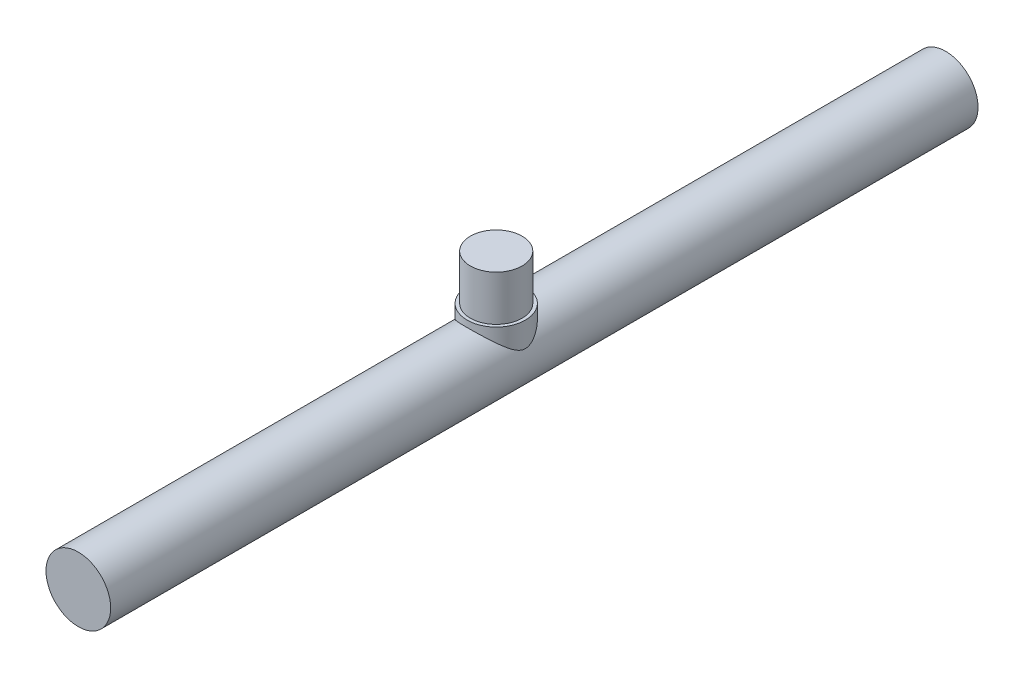
SolidWorks part; units mm, degrees
ref_plane "Front Plane" through (0, 0, 0) normal (0, 0, 1) x (1, 0, 0)
ref_plane "Top Plane" through (0, 0, 0) normal (0, 1, 0) x (1, 0, 0)
ref_plane "Right Plane" through (0, 0, 0) normal (1, 0, 0) x (0, 0, -1)
sketch "Sketch1" plane through (0, 0, 0) normal (0, 0, 1) x (1, 0, 0)
  circle A0 centre (0, 0) radius 5
  dimension "D1" = 10
extrude "Boss-Extrude1" add sketch "Sketch1" along normal blind 70
sketch "Sketch2" plane through (0, 0, 0) normal (0, 1, 0) x (1, 0, 0)
  circle A0 centre (0, -5.3867) radius 4.5
  dimension "D1" = 9
extrude "Boss-Extrude2" add sketch "Sketch2" along normal blind 6
sketch "Sketch3" plane through (0, 0, 0) normal (0, 0, -1) x (-1, 0, 0)
  circle A0 centre (0, 0) radius 5
extrude "Cut-Extrude2" cut sketch "Sketch3" against normal blind 0.8867
sketch "Sketch4" plane through (0, 6, 0) normal (0, 1, 0) x (1, 0, 0)
  circle A0 centre (0, -5.3867) radius 4
  dimension "D1" = 8
extrude "Boss-Extrude3" add sketch "Sketch4" along normal blind 7
sketch "Sketch5" plane through (0, 0, 0.8867) normal (0, 0, -1) x (-1, 0, 0)
  circle A0 centre (0, 0) radius 5 construction
  circle A1 centre (0, 0) radius 5
extrude "Boss-Extrude4" add sketch "Sketch5" along normal blind 65
